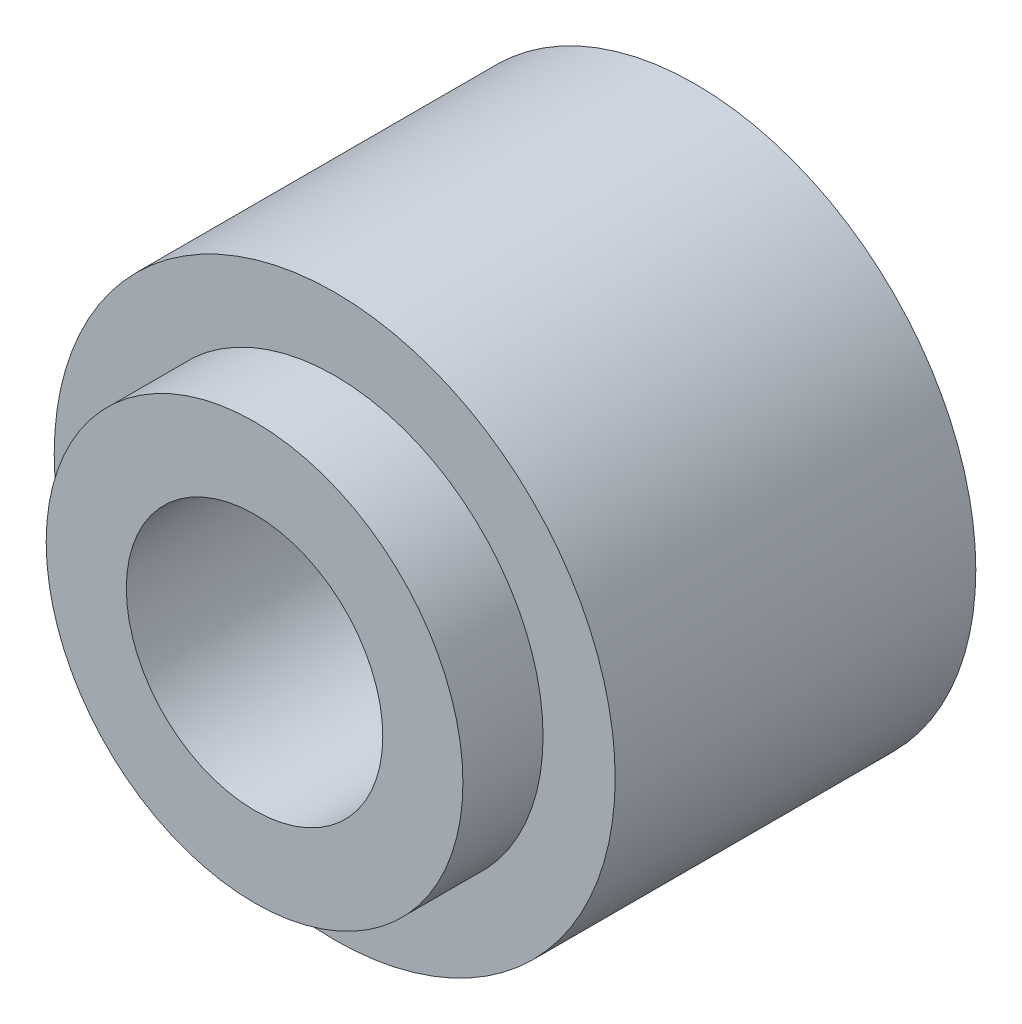
SolidWorks part; units mm, degrees
ref_plane "Спереди" through (0, 0, 0) normal (0, 0, 1) x (1, 0, 0)
ref_plane "Сверху" through (0, 0, 0) normal (0, 1, 0) x (1, 0, 0)
ref_plane "Справа" through (0, 0, 0) normal (1, 0, 0) x (0, 0, -1)
sketch "Эскиз1" plane through (0, 0, 0) normal (0, 0, 1) x (1, 0, 0)
  circle A0 centre (0, 0) radius 1.6
  circle A1 centre (0, 0) radius 3.5
  dimension "D1" = 3.2
  dimension "D2" = 7
extrude "Бобышка-Вытянуть1" add sketch "Эскиз1" along normal blind 5.5
sketch "Эскиз2" plane through (0, 0, 5.5) normal (0, 0, 1) x (1, 0, 0)
  circle A0 centre (0, 0) radius 2.6
  circle A1 centre (0, 0) radius 1.6 construction
  dimension "D1" = 1
extrude "Вырез-Вытянуть1" cut sketch "Эскиз2" against normal blind 1 flip side to cut
